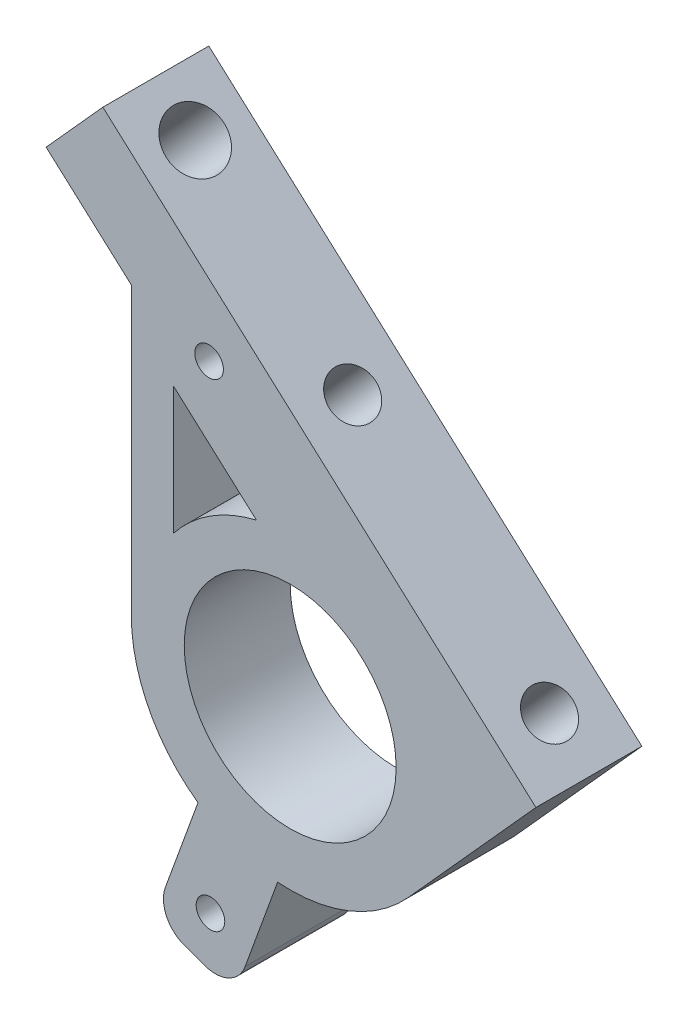
SolidWorks part; units mm, degrees
material "6061 Alloy"
ref_plane "Front Plane" through (0, 0, 0) normal (0, 0, 1) x (1, 0, 0)
ref_plane "Top Plane" through (0, 0, 0) normal (0, 1, 0) x (1, 0, 0)
ref_plane "Right Plane" through (0, 0, 0) normal (1, 0, 0) x (0, 0, -1)
sketch "Sketch1" plane through (0, 0, 0) normal (0, 0, 1) x (1, 0, 0)
  line L0 (-17.6814, 40.1418) -> (21.9261, 40.1418) construction
  line L1 (-15, 0) -> (-15, 26.9624)
  line L2 (-15, 26.9624) -> (-23.0345, 34.1967)
  line L3 (-23.0345, 34.1967) -> (-17.6814, 40.1418)
  line L4 (-17.6814, 40.1418) -> (23.1915, 3.3396)
  line L5 (23.1915, 3.3396) -> (17.8385, -2.6055)
  line L10 (17.8385, -2.6055) -> (11.1472, -10.037)
  line L11 (-15, 26.9624) -> (17.8385, -2.6055) construction
  circle A0 centre (0, 0) radius 10
  arc A1 (-15, 0) -> (11.1472, -10.037) centre (0, 0) ccw
  dimension "D3" = 20
  dimension "D4" = 5
  dimension "D1" = 42
  dimension "D2" = 8
  dimension "D7" = 55
extrude "3/8" add sketch "Sketch1" along normal blind 10
sketch "Sketch2" plane through (0, 0, 0) normal (0, 0, 1) x (1, 0, 0)
  line L0 (0, 0) -> (0, -7.8768) construction
  line L1 (-8.7033, -12.2169) -> (-1.1858, -14.9531)
  line L2 (-8.7033, -12.2169) -> (-12.8075, -23.4932)
  line L3 (-12.8075, -23.4932) -> (-5.29, -26.2294)
  line L4 (-1.1858, -14.9531) -> (-5.29, -26.2294)
  line L5 (-9.0488, -24.8613) -> (-4.9445, -13.585) construction
  line L6 (-10.7554, -17.8551) -> (-3.2379, -20.5912) construction
  arc A0 (-15, 0) -> (11.1472, -10.037) centre (0, 0) ccw construction
  point P360 (-6.9966, -19.2231)
  dimension "D1" = 12
  dimension "D2" = 8
  dimension "D3" = 110
extrude "Boss-Extrude2" add sketch "Sketch2" along normal up to surface (10 mm away) up to face at (-6.6377, 14.2697, 10)
sketch "Sketch3" plane through (0, 0, 10) normal (0, 0, 1) x (1, 0, 0)
  line L0 (0, 0) -> (-9.0488, -24.8613) construction
  line L1 (-12.8075, -23.4932) -> (-5.29, -26.2294) construction
  circle A0 centre (-7.5244, -20.6732) radius 1.35
  dimension "D2" = 2.7
  dimension "D1" = 22
extrude "M3_DRILL_or_Through" cut sketch "Sketch3" against normal up to surface (10 mm away) up to face at (-6.5272, 1.5509, 0)
fillet "Fillet1" radius 3 2 edges at (-5.29, -26.2294, 5) (-12.8075, -23.4932, 5)
sketch "Sketch4" plane through (12.0444, 13.3766, 0) normal (0.6691, 0.7431, 0) x (0.7431, -0.6691, 0)
  line L0 (-40, -5) -> (15, -5) construction
  line L1 (-40, -10) -> (-40, 0) construction
  line L2 (15, -10) -> (15, 0) construction
  circle A0 centre (-35, -5) radius 2.75
  dimension "D2" = 5.5
  dimension "D1" = 5
extrude "M5_through" cut sketch "Sketch4" against normal up to surface (8 mm away) up to face at (-19.0172, 30.5795, 5)
sketch "Sketch5" plane through (12.0444, 13.3766, 0) normal (0.6691, 0.7431, 0) x (0.7431, -0.6691, 0)
  line L0 (-35, -5) -> (10, -5) construction
  circle A0 centre (-15, -5) radius 2.2
  circle A1 centre (10, -5) radius 2.2
  dimension "D1" = 4.4
  dimension "D2" = 20
  dimension "D3" = 45
extrude "M5_DRILL" cut sketch "Sketch5" against normal blind 8
sketch "Sketch6" plane through (0, 0, 10) normal (0, 0, 1) x (1, 0, 0)
  line L0 (-11, 20.6695) -> (-11, 8.6603)
  line L1 (-11, 20.6695) -> (-3.185, 13.6329)
  line L2 (23.1915, 3.3396) -> (-17.6814, 40.1418) construction
  line L3 (-15, 26.9624) -> (-15, 0) construction
  arc A0 (-11, 8.6603) -> (-3.185, 13.6329) centre (0, 0) cw
  circle A1 centre (0, 0) radius 10 construction
  dimension "D3" = 4
  dimension "D1" = 10
  dimension "D2" = 4
extrude "Cut-Extrude4" cut sketch "Sketch6" against normal up to vertex (10 mm away) up to point (-17.6814, 40.1418, 0)
sketch "Sketch7" plane through (0, 0, 10) normal (0, 0, 1) x (1, 0, 0)
  line L0 (-11, 20.6695) -> (-4.3087, 28.101) construction
  line L1 (23.1915, 3.3396) -> (-17.6814, 40.1418) construction
  circle A0 centre (-7.6543, 24.3852) radius 1.35
  dimension "D1" = 2.7
extrude "M3_DRILL_or_Through2" cut sketch "Sketch7" against normal up to surface (10 mm away) up to face at (-8.5361, 14.5426, 0)
